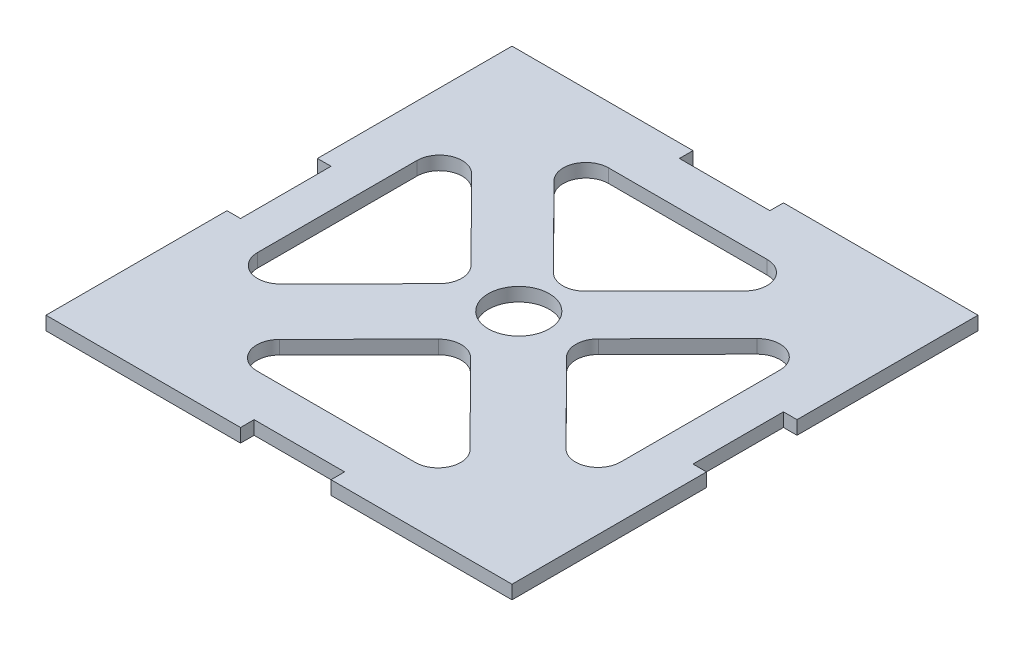
SolidWorks part; units mm, degrees
other "Markup1"
sketch "Sketch2" plane through (-50, 3, 50.5) normal (-0.0452, 0.9955, 0.0839) x (0.997, 0.0397, 0.066)
other "Markup2"
sketch "Sketch4" plane through (-50.5908, 3, 51.1584) normal (-0.0214, 0.9991, 0.0362) x (0.9834, 0.0145, 0.1809)
other "Markup3"
sketch "Sketch5" plane through (-51.5, 3, -51.5) normal (0, 1, 0) x (1, 0, 0)
other "Markup4"
sketch "Sketch6" plane through (-51.5, 3, -51.5) normal (0, 1, 0) x (1, 0, 0)
ref_plane "Front Plane" through (0, 0, 0) normal (0, 0, 1) x (1, 0, 0)
ref_plane "Top Plane" through (0, 0, 0) normal (0, 1, 0) x (1, 0, 0)
ref_plane "Right Plane" through (0, 0, 0) normal (1, 0, 0) x (0, 0, -1)
sketch "Sketch1" plane through (0, 0, 0) normal (0, 1, 0) x (1, 0, 0)
  line L0 (-29.5455, -40.3709) -> (-4.0436, -14.7089)
  line L1 (-51.5, -53) -> (-10, -53)
  line L5 (-4.7486, -4.7784) -> (4.7486, 4.7784) construction
  line L6 (-4.7486, 4.7784) -> (4.7486, -4.7784) construction
  line L7 (-40.119, -40.3709) -> (40.119, -40.3709)
  line L8 (-40.119, -40.3709) -> (-40.119, 37.3709)
  line L9 (-40.119, 37.3709) -> (40.119, 37.3709)
  line L10 (40.119, -40.3709) -> (40.119, 37.3709)
  line L11 (-4.7486, -4.7784) -> (4.7486, 4.7784) construction
  line L12 (-4.7486, 4.7784) -> (4.7486, -4.7784) construction
  line L13 (-34.0986, -23.6727) -> (-14.6833, -4.1355)
  line L14 (40.119, -29.7309) -> (14.6833, -4.1355)
  line L15 (23.9097, -34.6997) -> (4.0436, -14.7089)
  line L16 (-34.0986, -23.6727) -> (-40.119, -29.7309)
  line L17 (23.9097, -34.6997) -> (29.5455, -40.3709)
  line L19 (-14.6833, -4.1355) -> (-10.5736, 0)
  line L20 (-14.6833, 4.1355) -> (-10.5736, 0)
  line L21 (-14.6833, 4.1355) -> (-40.119, 29.7309)
  line L22 (-51.5, -13) -> (-51.5, -53)
  line L23 (14.6833, 4.1355) -> (40.119, 29.7309)
  line L24 (-4.0436, 11.7089) -> (-0.0253, 7.6654)
  line L25 (4.0436, 11.7089) -> (29.5455, 37.3709)
  line L26 (-4.0436, 11.7089) -> (-29.5455, 37.3709)
  line L27 (4.0436, 11.7089) -> (-0.0253, 7.6654)
  line L44 (10, 50) -> (51.5, 50)
  line L49 (6.7367, 0) -> (-6.7367, 0) construction
  line L70 (-51.5, 8.5) -> (-51.5, 50)
  line L78 (11.5, -53) -> (51.5, -53)
  line L93 (51.5, -53) -> (51.5, -11.5)
  line L112 (51.5, 10) -> (51.5, 50)
  line L141 (-51.5, 50) -> (-11.5, 50)
  line L142 (-40.119, -1.5) -> (40.119, -1.5) construction
  line L143 (0, 6.7367) -> (0, -6.7367) construction
  line L144 (-4.0436, -14.7089) -> (0, -10.6399)
  line L145 (4.0436, -14.7089) -> (0, -10.6399)
  line L146 (14.6833, -4.1355) -> (10.5736, 0)
  line L147 (14.6833, 4.1355) -> (10.5736, 0)
  line L148 (51.5, 10) -> (48.5, 10) construction
  line L149 (0, -40.3709) -> (0, 37.3709) construction
  line L150 (51.5, -10) -> (48.5, -10) construction
  line L151 (51.5, 10) -> (48.5, 10)
  line L152 (51.5, -10) -> (48.5, -10)
  line L153 (51.5, -11.5) -> (51.5, -10)
  line L154 (48.5, -10) -> (48.5, 10)
  line L155 (-8.5, -53) -> (-8.5, -50) construction
  line L156 (11.5, -53) -> (11.5, -50) construction
  line L157 (-8.5, -53) -> (-8.5, -50)
  line L158 (11.5, -53) -> (11.5, -50)
  line L159 (-10, -53) -> (-8.5, -53)
  line L160 (-8.5, -50) -> (11.5, -50)
  line L161 (-51.5, 7) -> (-48.5, 7) construction
  line L162 (-51.5, -13) -> (-48.5, -13) construction
  line L163 (-51.5, 7) -> (-48.5, 7)
  line L164 (-51.5, -13) -> (-48.5, -13)
  line L165 (-48.5, -13) -> (-48.5, 7)
  line L166 (-51.5, 7) -> (-51.5, 8.5)
  line L167 (-11.5, 50) -> (-11.5, 47) construction
  line L168 (-11.5, 50) -> (-11.5, 47)
  line L169 (-11.5, 47) -> (8.5, 47)
  line L171 (8.5, 47) -> (48.5, 47)
  line L172 (48.5, 47) -> (48.5, 50)
  line L173 (48.5, 50) -> (8.5, 50)
  line L174 (8.5, 50) -> (8.5, 47)
  line L176 (48.5, 47) -> (48.5, 50)
  line L177 (48.5, 50) -> (8.5, 50)
  line L178 (8.5, 50) -> (8.5, 47)
  circle A0 centre (0, 0) radius 6.7367
  point P0 (0, 0)
  point P6 (0, 0)
  dimension "D1" = 0
extrude "Boss-Extrude1" add sketch "Sketch1" along normal blind 3
fillet "Fillet1" radius 5 8 edges at (-29.5455, 1.5, -37.3709) (29.5455, 1.5, -37.3709) (40.119, 1.5, -29.7309) (40.119, 1.5, 29.7309) (29.5455, 1.5, 40.3709) (-29.5455, 1.5, 40.3709) (-40.119, 1.5, -29.7309) (-40.119, 1.5, 29.7309)
fillet "Fillet2" radius 5 4 edges at (0, 1.5, 10.6399) (10.5736, 1.5, 0) (-0.0253, 1.5, -7.6654) (-10.5736, 1.5, 0)
